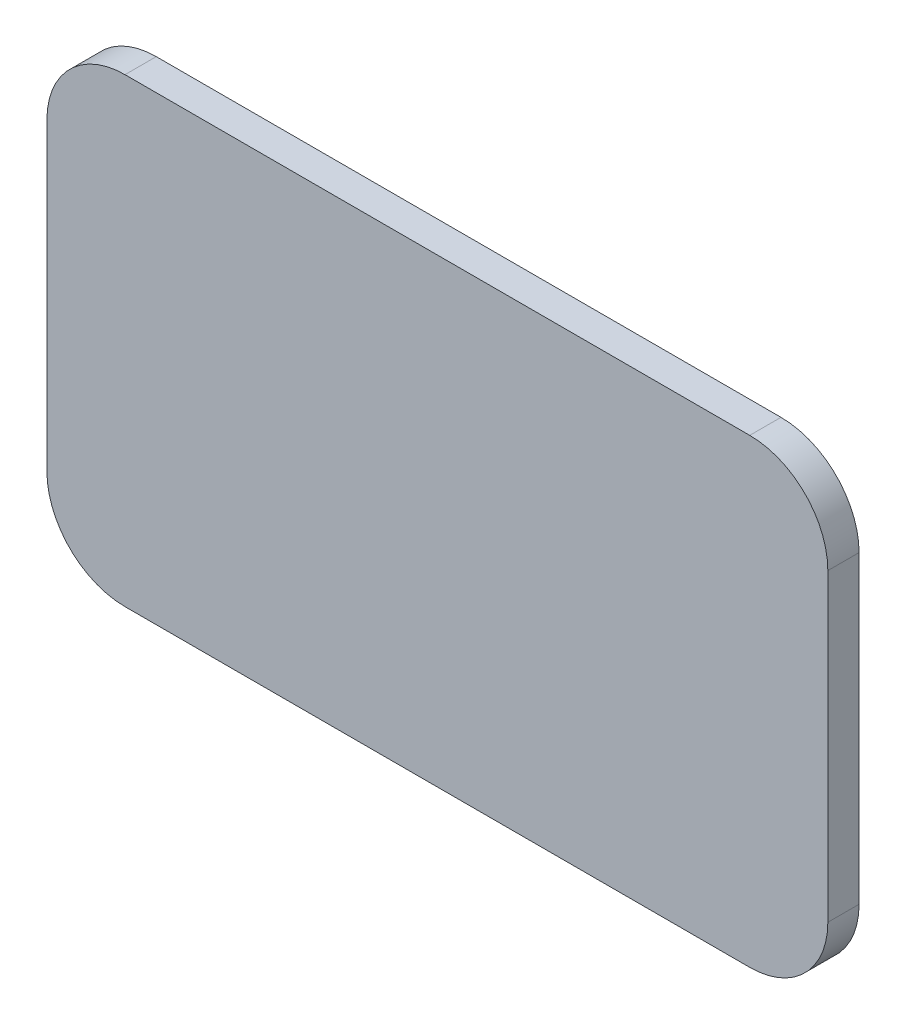
SolidWorks part; units mm, degrees
ref_plane "Front Plane" through (0, 0, 0) normal (0, 0, 1) x (1, 0, 0)
ref_plane "Top Plane" through (0, 0, 0) normal (0, 1, 0) x (1, 0, 0)
ref_plane "Right Plane" through (0, 0, 0) normal (1, 0, 0) x (0, 0, -1)
sketch "Sketch1" plane through (0, 0, 0) normal (0, 0, 1) x (1, 0, 0)
  line L1 (-46, -25.5) -> (46, -25.5)
  line L2 (-46, -25.5) -> (-46, 25.5)
  line L3 (-46, 25.5) -> (46, 25.5)
  line L4 (46, -25.5) -> (46, 25.5)
  line L5 (-46, -25.5) -> (46, 25.5) construction
  line L6 (-46, 25.5) -> (46, -25.5) construction
  point P0 (0, 0)
  dimension "D1" = 92
  dimension "D2" = 51
extrude "Boss-Extrude1" add sketch "Sketch1" along normal blind 2
fillet "Fillet1" radius 6 4 edges at (-46, -25.5, 1) (-46, 25.5, 1) (46, -25.5, 1) (46, 25.5, 1)
sketch "Sketch2" plane through (0, 0, 2) normal (0, 0, 1) x (1, 0, 0)
  line L0 (-40, -29.5) -> (40, -29.5)
  line L1 (50, -19.5) -> (50, 19.5)
  line L2 (40, 29.5) -> (-40, 29.5)
  line L3 (-50, 19.5) -> (-50, -19.5)
  line L4 (-46, 19.5) -> (-46, -19.5)
  line L5 (-40, -25.5) -> (40, -25.5)
  line L6 (46, -19.5) -> (46, 19.5)
  line L7 (40, 25.5) -> (-40, 25.5)
  line L8 (-46, 19.5) -> (-46, -19.5)
  line L9 (-40, -25.5) -> (40, -25.5)
  line L10 (46, -19.5) -> (46, 19.5)
  line L11 (40, 25.5) -> (-40, 25.5)
  arc A0 (40, -29.5) -> (50, -19.5) centre (40, -19.5) ccw
  arc A1 (50, 19.5) -> (40, 29.5) centre (40, 19.5) ccw
  arc A2 (-40, 29.5) -> (-50, 19.5) centre (-40, 19.5) ccw
  arc A3 (-50, -19.5) -> (-40, -29.5) centre (-40, -19.5) ccw
  arc A4 (-46, -19.5) -> (-40, -25.5) centre (-40, -19.5) ccw
  arc A5 (40, -25.5) -> (46, -19.5) centre (40, -19.5) ccw
  arc A6 (46, 19.5) -> (40, 25.5) centre (40, 19.5) ccw
  arc A7 (-40, 25.5) -> (-46, 19.5) centre (-40, 19.5) ccw
  arc A8 (-46, -19.5) -> (-40, -25.5) centre (-40, -19.5) ccw
  arc A9 (40, -25.5) -> (46, -19.5) centre (40, -19.5) ccw
  arc A10 (46, 19.5) -> (40, 25.5) centre (40, 19.5) ccw
  arc A11 (-40, 25.5) -> (-46, 19.5) centre (-40, 19.5) ccw
  dimension "D1" = 0
  dimension "D2" = 4
extrude "Boss-Extrude2" add sketch "Sketch2" against normal blind 4
ref_plane "Plane1" through (0, 0, 0) normal (0, 1, 0) x (1, 0, 0)
sketch "Sketch3" plane through (0, 0, 0) normal (0, 1, 0) x (1, 0, 0)
  line L0 (50, 2) -> (50, -2) construction
  line L1 (-41, 0) -> (-38, 0)
  line L2 (-41, 0) -> (-41, 10)
  line L3 (-41, 10) -> (-38, 10)
  line L4 (-38, 0) -> (-38, 10)
  line L5 (41, 0) -> (38, 0)
  line L6 (41, 0) -> (41, 10)
  line L7 (41, 10) -> (38, 10)
  line L8 (38, 0) -> (38, 10)
  line L9 (-50, 2) -> (-50, -2) construction
  line L10 (-40, 0) -> (40, 0) construction
  circle A0 centre (-39.8, 8.5) radius 1.5
  circle A1 centre (39.8, 8.5) radius 1.5
  dimension "D5" = 3
  dimension "D7" = 3
  dimension "D1" = 9
  dimension "D2" = 9
  dimension "D3" = 10
  dimension "D4" = 3
  dimension "D6" = 1.2
  dimension "D8" = 1.2
extrude "Boss-Extrude3" add sketch "Sketch3" along normal mid plane 20 contours A1 L7 L8 L5 L6 | L6 A1 | L6 A1 | A0 L2 L1 L4 L3 | A0 L2 | L2 A0
sketch "Sketch4" plane through (0, 0, -2) normal (0, 0, -1) x (-1, 0, 0)
  line L0 (-40, 25.5) -> (40, 25.5) construction
  line L1 (-46, -19.5) -> (-46, 19.5) construction
  line L2 (46, 19.5) -> (46, -19.5) construction
  line L3 (40, -25.5) -> (-40, -25.5) construction
  line L4 (-40, 25.5) -> (40, 25.5)
  line L5 (-46, -19.5) -> (-46, 19.5)
  line L6 (46, 19.5) -> (46, -19.5)
  line L7 (40, -25.5) -> (-40, -25.5)
  line L12 (46.1, -19.5) -> (46.1, 19.5)
  line L13 (40, 25.6) -> (-40, 25.6)
  line L14 (-46.1, 19.5) -> (-46.1, -19.5)
  line L15 (-40, -25.6) -> (40, -25.6)
  line L16 (46.1, -19.5) -> (46.1, 19.5)
  line L17 (40, 25.6) -> (-40, 25.6)
  line L18 (-46.1, 19.5) -> (-46.1, -19.5)
  line L19 (-40, -25.6) -> (40, -25.6)
  arc A0 (-40, 25.5) -> (-46, 19.5) centre (-40, 19.5) ccw construction
  arc A1 (46, 19.5) -> (40, 25.5) centre (40, 19.5) ccw construction
  arc A2 (-46, -19.5) -> (-40, -25.5) centre (-40, -19.5) ccw construction
  arc A3 (40, -25.5) -> (46, -19.5) centre (40, -19.5) ccw construction
  arc A4 (-40, 25.5) -> (-46, 19.5) centre (-40, 19.5) ccw
  arc A5 (46, 19.5) -> (40, 25.5) centre (40, 19.5) ccw
  arc A6 (-46, -19.5) -> (-40, -25.5) centre (-40, -19.5) ccw
  arc A7 (40, -25.5) -> (46, -19.5) centre (40, -19.5) ccw
  arc A12 (40, -25.6) -> (46.1, -19.5) centre (40, -19.5) ccw
  arc A13 (46.1, 19.5) -> (40, 25.6) centre (40, 19.5) ccw
  arc A14 (-40, 25.6) -> (-46.1, 19.5) centre (-40, 19.5) ccw
  arc A15 (-46.1, -19.5) -> (-40, -25.6) centre (-40, -19.5) ccw
  arc A16 (40, -25.6) -> (46.1, -19.5) centre (40, -19.5) ccw
  arc A17 (46.1, 19.5) -> (40, 25.6) centre (40, 19.5) ccw
  arc A18 (-40, 25.6) -> (-46.1, 19.5) centre (-40, 19.5) ccw
  arc A19 (-46.1, -19.5) -> (-40, -25.6) centre (-40, -19.5) ccw
  dimension "D1" = 3.9
extrude "Cut-Extrude2" cut sketch "Sketch4" against normal up to surface (2 mm away) up to face at (-39.5, 0, 0)
